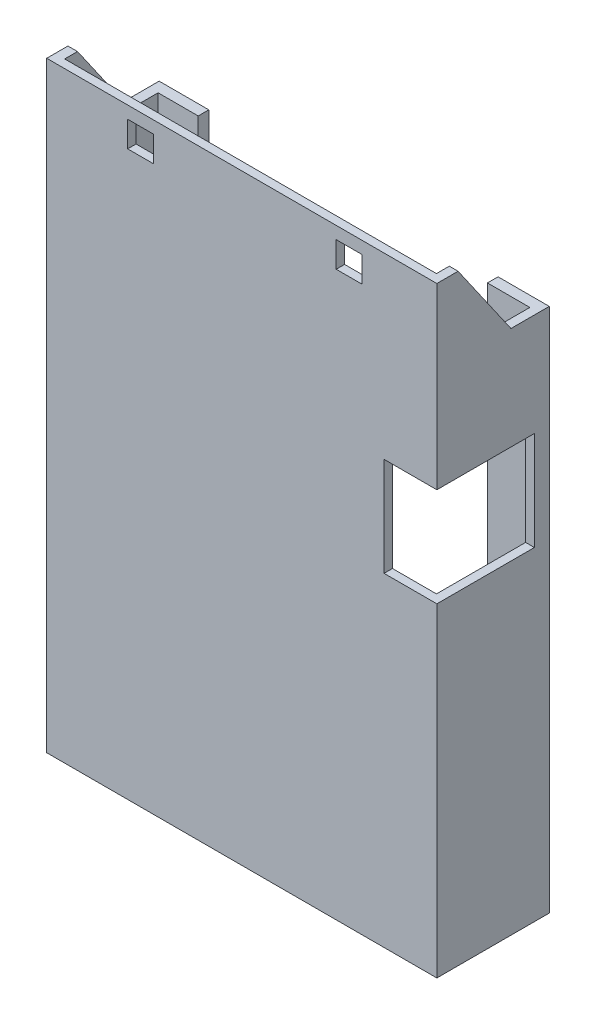
SolidWorks part; units mm, degrees
ref_plane "Front Plane" through (0, 0, 0) normal (0, 0, 1) x (1, 0, 0)
ref_plane "Top Plane" through (0, 0, 0) normal (0, 1, 0) x (1, 0, 0)
ref_plane "Right Plane" through (0, 0, 0) normal (1, 0, 0) x (0, 0, -1)
sketch "Sketch4" plane through (0, 0, 0) normal (0, 0, 1) x (1, 0, 0)
  line L1 (60, 92.5) -> (-60, 92.5)
  line L2 (60, 92.5) -> (60, -92.5)
  line L3 (60, -92.5) -> (-60, -92.5)
  line L4 (-60, 92.5) -> (-60, -92.5)
  line L5 (60, 92.5) -> (-60, -92.5) construction
  line L6 (60, -92.5) -> (-60, 92.5) construction
  point P0 (0, 0)
  point P6 (0, 0)
  point P7 (-15.8569, -25.3126)
  point P8 (16.8045, -25.5897)
  point P9 (17.7972, -30.0369)
  point P10 (29.2696, -44.5391)
  point P11 (43.4871, -56.8397)
  point P12 (0, 0)
  point P13 (-63.8413, -99.179)
  point P14 (-73.2949, -113.5223)
  dimension "D1" = 120
  dimension "D2" = 185
extrude "Boss-Extrude2" add sketch "Sketch4" along normal blind 34.4794 and the other way blind 0.1
sketch "Sketch7" plane through (0, 0, -0.1) normal (0, 0, -1) x (-1, 0, 0)
  line L0 (-60, 92.5) -> (60, 92.5) construction
  line L1 (-44.2434, 92.5) -> (44.7217, 92.5)
  line L2 (-44.2434, 92.5) -> (-44.2434, -76.29)
  line L3 (-44.2434, -76.29) -> (44.7217, -76.29)
  line L4 (44.7217, 92.5) -> (44.7217, -76.29)
extrude "Cut-Extrude1" cut sketch "Sketch7" against normal blind 32
sketch "Sketch8" plane through (0, -76.29, 0) normal (0, 1, 0) x (1, 0, 0)
  line L1 (-18.8197, -3.2559) -> (19.2992, -3.2559)
  line L2 (-18.8197, -3.2559) -> (-18.8197, -29.2679)
  line L3 (-18.8197, -29.2679) -> (19.2992, -29.2679)
  line L4 (19.2992, -3.2559) -> (19.2992, -29.2679)
extrude "Cut-Extrude2" cut sketch "Sketch8" against normal blind 32
sketch "Sketch12" plane through (0, 92.5, 0) normal (0, 1, 0) x (1, 0, 0)
  line L1 (-44.7217, -31.9) -> (-57.0584, -31.9)
  line L2 (-44.7217, -31.9) -> (-44.7217, -3.1648)
  line L3 (-44.7217, -3.1648) -> (-57.0584, -3.1648)
  line L4 (-57.0584, -31.9) -> (-57.0584, -3.1648)
  line L5 (44.2434, -31.9) -> (57.2982, -31.9)
  line L6 (44.2434, -31.9) -> (44.2434, -3.1648)
  line L7 (44.2434, -3.1648) -> (57.2982, -3.1648)
  line L8 (57.2982, -31.9) -> (57.2982, -3.1648)
extrude "Cut-Extrude10" cut sketch "Sketch12" against normal blind 169
sketch "Sketch13" plane through (60, 0, 0) normal (1, 0, 0) x (0, 0, -1)
  line L0 (-27.9521, 92.5) -> (-11.6897, 69.1154)
  line L1 (0.1, 92.5) -> (-34.4794, 92.5) construction
  line L2 (-11.6897, 69.1154) -> (0.1, 69.1154)
  line L3 (0.1, -92.5) -> (0.1, 92.5) construction
extrude "Cut-Extrude11" cut sketch "Sketch13" against normal blind 120 and the other way through all
sketch "Sketch14" plane through (0, 0, 31.9) normal (0, 0, -1) x (-1, 0, 0)
  line L1 (-36.93, 88.7053) -> (-29.0366, 88.7053)
  line L2 (-36.93, 88.7053) -> (-36.93, 80.8118)
  line L3 (-36.93, 80.8118) -> (-29.0366, 80.8118)
  line L4 (-29.0366, 88.7053) -> (-29.0366, 80.8118)
  line L5 (35.1022, 88.7053) -> (27.2088, 88.7053)
  line L6 (35.1022, 88.7053) -> (35.1022, 80.8118)
  line L7 (35.1022, 80.8118) -> (27.2088, 80.8118)
  line L8 (27.2088, 88.7053) -> (27.2088, 80.8118)
extrude "Cut-Extrude13" cut sketch "Sketch14" against normal blind 120
sketch "Sketch16" plane through (0, 0, 34.4794) normal (0, 0, 1) x (1, 0, 0)
  line L0 (60, -92.5) -> (60, 92.5) construction
  line L1 (60, 37.5471) -> (43.7651, 37.5471)
  line L2 (60, 37.5471) -> (60, 7.1746)
  line L3 (60, 7.1746) -> (43.7651, 7.1746)
  line L4 (43.7651, 37.5471) -> (43.7651, 7.1746)
extrude "Cut-Extrude15" cut sketch "Sketch16" against normal blind 30
